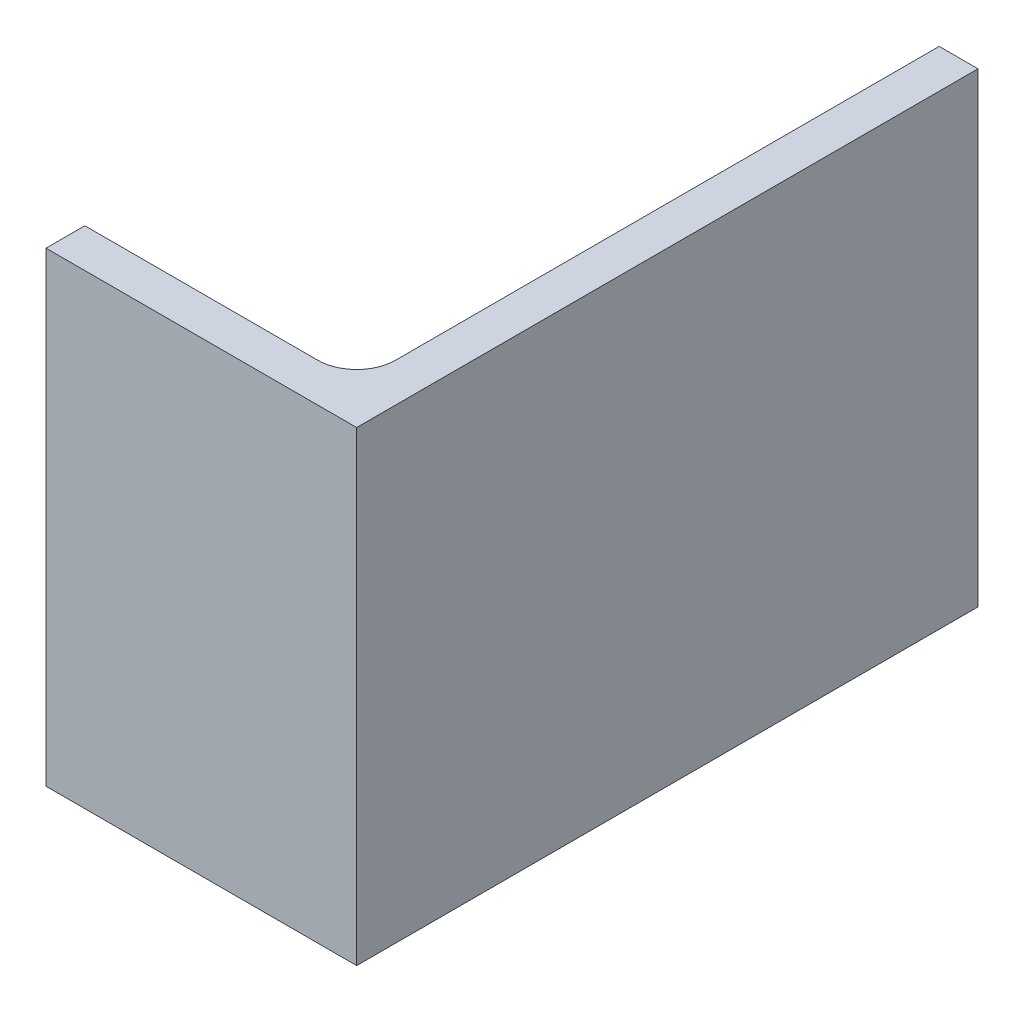
SolidWorks part; units mm, degrees
material "PET"
ref_plane "Front Plane" through (0, 0, 0) normal (0, 0, 1) x (1, 0, 0)
ref_plane "Top Plane" through (0, 0, 0) normal (0, 1, 0) x (1, 0, 0)
ref_plane "Right Plane" through (0, 0, 0) normal (1, 0, 0) x (0, 0, -1)
sketch "Sketch1" plane through (0, 0, 0) normal (0, 0, 1) x (1, 0, 0)
  line L1 (-12.7, 19.05) -> (12.7, 19.05)
  line L2 (-12.7, 19.05) -> (-12.7, -19.05)
  line L3 (-12.7, -19.05) -> (12.7, -19.05)
  line L4 (12.7, 19.05) -> (12.7, -19.05)
  line L5 (-12.7, 19.05) -> (12.7, -19.05) construction
  line L6 (-12.7, -19.05) -> (12.7, 19.05) construction
  point P0 (0, 0)
  dimension "D1" = 38.1
  dimension "D2" = 25.4
extrude "Boss-Extrude1" add sketch "Sketch1" against normal blind 50.8
shell "Shell1" thickness 3.175
fillet "Fillet1" radius 3.175 3 edges at (9.525, 1.5875, -3.175) (9.525, -15.875, -26.9875) (-1.5875, -15.875, -3.175)
